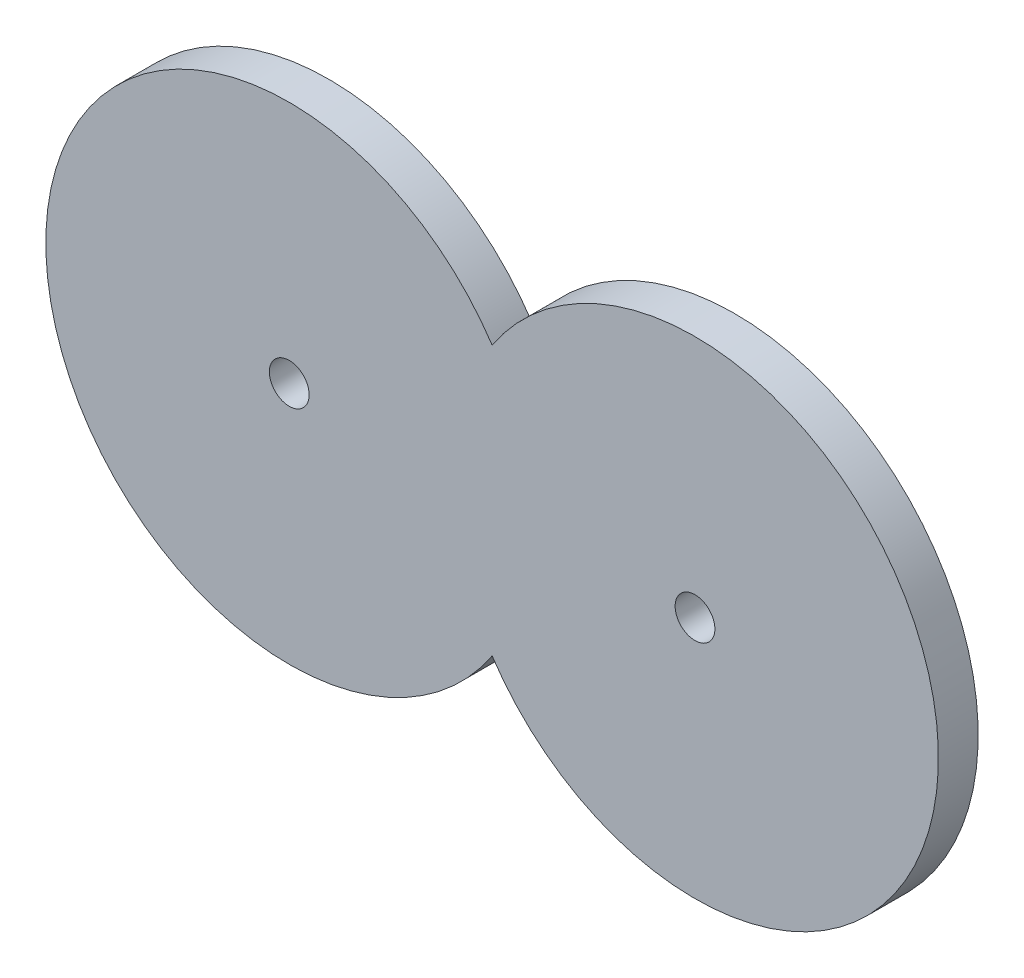
SolidWorks part; units mm, degrees
ref_plane "Front Plane" through (0, 0, 0) normal (0, 0, 1) x (1, 0, 0)
ref_plane "Top Plane" through (0, 0, 0) normal (0, 1, 0) x (1, 0, 0)
ref_plane "Right Plane" through (0, 0, 0) normal (1, 0, 0) x (0, 0, -1)
sketch "Sketch1" plane through (0, 0, 0) normal (0, 0, 1) x (1, 0, 0)
  line L1 (0, 0) -> (63.5, 0)
  line L2 (0, 0) -> (0, 38.1)
  line L3 (0, 38.1) -> (63.5, 38.1)
  line L4 (63.5, 0) -> (63.5, 38.1)
  circle A0 centre (0, 19.05) radius 3.1115
  circle A1 centre (63.5, 19.05) radius 3.1115
  circle A2 centre (0, 19.05) radius 38.1
  circle A3 centre (63.5, 19.05) radius 38.1
  dimension "D3" = 6.223
  dimension "D4" = 76.2
  dimension "D1" = 38.1
  dimension "D2" = 63.5
extrude "Boss-Extrude1" add sketch "Sketch1" along normal blind 6.223 contours A3 L3 L2 A0 L1 | A3 A2 L1 L2 A0 L3 | A2 A3 L3 | A2 A3 L3 L4 A1 L1 | L3 A3 L1 A2 | A2 L1 L4 A1 L3 | L1 A3 A2
